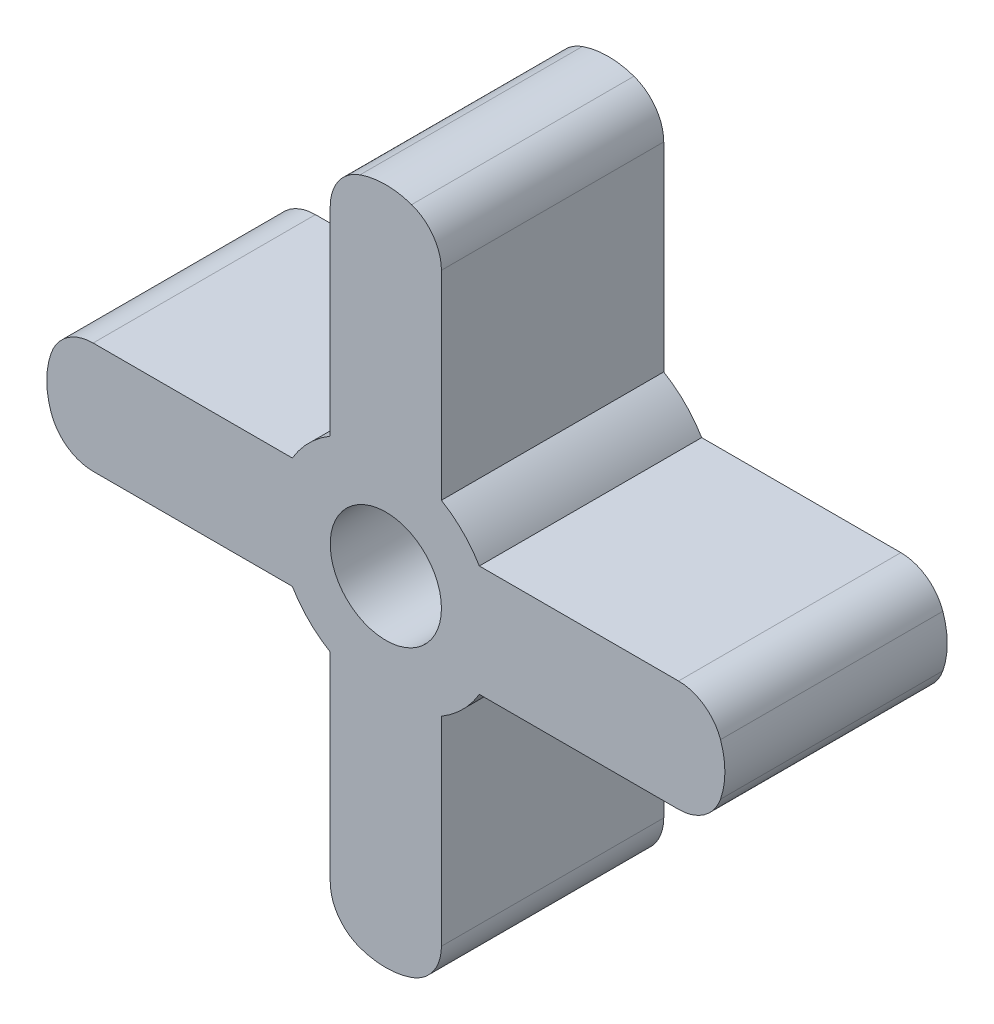
SolidWorks part; units mm, degrees
material "ABS"
ref_plane "Front Plane" through (0, 0, 0) normal (0, 0, 1) x (1, 0, 0)
ref_plane "Top Plane" through (0, 0, 0) normal (0, 1, 0) x (1, 0, 0)
ref_plane "Right Plane" through (0, 0, 0) normal (1, 0, 0) x (0, 0, -1)
sketch "Sketch3" plane through (0, 0, 0) normal (0, 0, 1) x (1, 0, 0)
  line L0 (-2.5, 4.2058) -> (-2.5, 14.2058)
  line L1 (0, 15.25) -> (0, 5.2725) construction
  line L2 (2.5, 4.2058) -> (2.5, 14.2058)
  line L3 (4.2058, 2.5) -> (14.2058, 2.5)
  line L4 (4.2058, -2.5) -> (14.2058, -2.5)
  line L5 (2.5, -4.2058) -> (2.5, -14.2058)
  line L6 (-2.5, -4.2058) -> (-2.5, -14.2058)
  line L7 (-4.2058, -2.5) -> (-14.2058, -2.5)
  line L8 (-4.2058, 2.5) -> (-14.2058, 2.5)
  line L9 (0, -4.8927) -> (0, -15.25) construction
  arc A0 (-2.5, 4.2058) -> (-4.2058, 2.5) centre (0, 0) ccw
  arc A1 (-2.5, 14.2058) -> (2.5, 14.2058) centre (0, 11.7352) cw
  arc A2 (14.2058, 2.5) -> (14.2058, -2.5) centre (11.7352, 0) cw
  arc A3 (2.5, -14.2058) -> (-2.5, -14.2058) centre (0, -11.7352) cw
  arc A4 (-14.2058, -2.5) -> (-14.2058, 2.5) centre (-11.7352, 0) cw
  arc A5 (4.2058, 2.5) -> (2.5, 4.2058) centre (0, 0) ccw
  arc A6 (-4.2058, -2.5) -> (-2.5, -4.2058) centre (0, 0) ccw
  arc A7 (2.5, -4.2058) -> (4.2058, -2.5) centre (0, 0) ccw
  point P12 (-15.25, 0)
  point P28 (0, 0)
  dimension "D1" = 5
  dimension "D2" = 15.25
  dimension "D4" = 10
  dimension "D3" = 4
extrude "Boss-Extrude1" add sketch "Sketch3" along normal blind 10
fillet "Fillet1" radius 2 8 edges at (14.2058, 2.5, 5) (14.2058, -2.5, 5) (2.5, -14.2058, 5) (-2.5, -14.2058, 5) (-14.2058, -2.5, 5) (-14.2058, 2.5, 5) (2.5, 14.2058, 5) (-2.5, 14.2058, 5)
sketch "Sketch4" plane through (0, 0, 0) normal (0, 0, 1) x (1, 0, 0)
  circle A0 centre (0, 0) radius 2.5
extrude "Cut-Extrude1" cut sketch "Sketch4" along normal through all both and the other way through all
